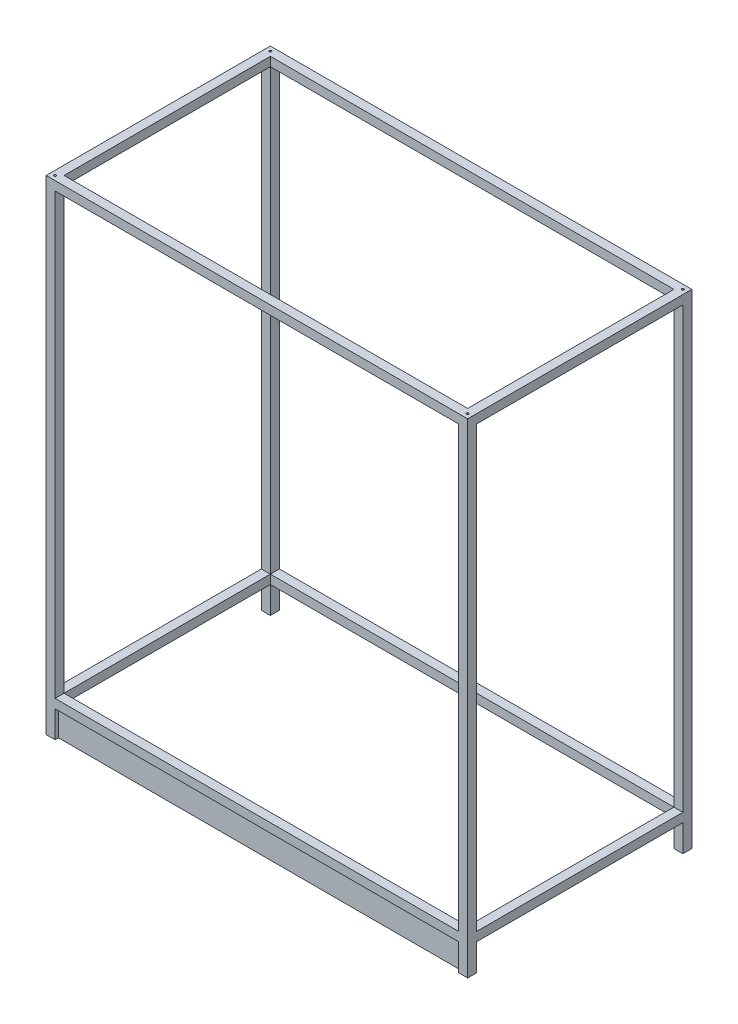
SolidWorks part; units mm, degrees
ref_plane "Front Plane" through (0, 0, 0) normal (0, 0, 1) x (1, 0, 0)
ref_plane "Top Plane" through (0, 0, 0) normal (0, 1, 0) x (1, 0, 0)
ref_plane "Right Plane" through (0, 0, 0) normal (1, 0, 0) x (0, 0, -1)
sketch "Sketch1" plane through (0, 0, 0) normal (0, 0, 1) x (1, 0, 0)
  line L1 (0, 0) -> (1193.8, 0)
  line L2 (0, 0) -> (0, 1371.6)
  line L3 (0, 1371.6) -> (1193.8, 1371.6)
  line L4 (1193.8, 0) -> (1193.8, 1371.6)
  dimension "D1" = 1193.8
  dimension "D2" = 1371.6
extrude "Extrude1" add sketch "Sketch1" along normal blind 635
sketch "Sketch2" plane through (0, 1371.6, 0) normal (0, 1, 0) x (1, 0, 0)
  line L0 (25.4, -609.6) -> (25.4, -635)
  line L1 (-656.59, 0) -> (656.59, 0) construction
  line L2 (25.4, 0) -> (25.4, -25.4)
  line L3 (1193.8, 0) -> (0, 0) construction
  line L4 (0, -635) -> (0, 0) construction
  line L5 (1168.4, 0) -> (1168.4, -25.4)
  line L6 (0, -609.6) -> (25.4, -609.6)
  line L7 (1193.8, -635) -> (1193.8, 0) construction
  line L8 (0, -25.4) -> (25.4, -25.4)
  line L9 (1193.8, -635) -> (0, -635) construction
  line L10 (1168.4, -25.4) -> (1193.8, -25.4)
  line L11 (1168.4, -609.6) -> (1193.8, -609.6)
  line L12 (1168.4, -609.6) -> (1168.4, -635)
  line L14 (1168.4, 0) -> (25.4, 0)
  line L15 (1193.8, -25.4) -> (1193.8, -609.6)
  line L16 (1168.4, -635) -> (25.4, -635)
  line L17 (0, -25.4) -> (0, -609.6)
sketch "Sketch4" plane through (0, 1371.6, 0) normal (0, 1, 0) x (1, 0, 0)
extrude "Extrude4" cut sketch "Sketch2" against normal blind 1270
sketch "Sketch6" plane through (0, 0, 25.4) normal (0, 0, 1) x (1, 0, 0)
  line L0 (0, 1371.6) -> (0, 1346.2)
  line L1 (0, 101.6) -> (0, 1371.6) construction
  line L2 (0, 1346.2) -> (25.4, 1346.2)
  line L3 (25.4, 101.6) -> (25.4, 1371.6) construction
  line L4 (25.4, 1346.2) -> (25.4, 1371.6)
  line L5 (25.4, 1371.6) -> (0, 1371.6) construction
  line L6 (25.4, 1371.6) -> (0, 1371.6)
  dimension "D1" = 25.4
extrude "Extrude5" add sketch "Sketch6" along normal up to surface (584.2 mm away) up to face at (12.7, 736.6, 609.6)
sketch "Sketch8" plane through (25.4, 0, 0) normal (1, 0, 0) x (0, 0, -1)
  line L1 (-635, 1371.6) -> (-609.6, 1371.6)
  line L2 (-635, 1371.6) -> (-635, 1346.2)
  line L3 (-635, 1346.2) -> (-609.6, 1346.2)
  line L4 (-609.6, 1371.6) -> (-609.6, 1346.2)
extrude "Extrude6" add sketch "Sketch8" along normal up to surface (1143 mm away) up to face at (1168.4, 736.6, 622.3)
sketch "Sketch9" plane through (0, 0, 609.6) normal (0, 0, -1) x (-1, 0, 0)
  line L1 (-1193.8, 1371.6) -> (-1168.4, 1371.6)
  line L2 (-1193.8, 1371.6) -> (-1193.8, 1346.2)
  line L3 (-1193.8, 1346.2) -> (-1168.4, 1346.2)
  line L4 (-1168.4, 1371.6) -> (-1168.4, 1346.2)
extrude "Extrude7" add sketch "Sketch9" along normal up to surface (584.2 mm away) up to face at (1181.1, 736.6, 25.4)
sketch "Sketch10" plane through (1168.4, 0, 0) normal (-1, 0, 0) x (0, 0, 1)
  line L1 (0, 1371.6) -> (25.4, 1371.6)
  line L2 (0, 1371.6) -> (0, 1346.2)
  line L3 (0, 1346.2) -> (25.4, 1346.2)
  line L4 (25.4, 1371.6) -> (25.4, 1346.2)
extrude "Extrude8" add sketch "Sketch10" along normal up to surface (1143 mm away) up to face at (25.4, 723.9, 622.3)
shell "Shell2" thickness 25.4
sketch "Sketch11" plane through (25.4, 0, 0) normal (1, 0, 0) x (0, 0, -1)
  line L1 (-25.4, 76.2) -> (-609.6, 76.2)
  line L2 (-25.4, 76.2) -> (-25.4, 0)
  line L3 (-25.4, 0) -> (-609.6, 0)
  line L4 (-609.6, 76.2) -> (-609.6, 0)
sketch "Sketch12" plane through (0, 0, 25.4) normal (0, 0, 1) x (1, 0, 0)
  line L1 (25.4, 76.2) -> (1168.4, 76.2)
  line L2 (25.4, 76.2) -> (25.4, 0)
  line L3 (25.4, 0) -> (1168.4, 0)
  line L4 (1168.4, 76.2) -> (1168.4, 0)
sketch "Sketch13" plane through (1168.4, 0, 0) normal (-1, 0, 0) x (0, 0, 1)
  line L1 (609.6, 76.2) -> (25.4, 76.2)
  line L2 (609.6, 76.2) -> (609.6, 0)
  line L3 (609.6, 0) -> (25.4, 0)
  line L4 (25.4, 76.2) -> (25.4, 0)
sketch "Sketch14" plane through (0, 0, 609.6) normal (0, 0, -1) x (-1, 0, 0)
  line L2 (-25.4, 0) -> (-1168.4, 0)
  line L3 (-25.4, 0) -> (-25.4, 76.2)
  line L4 (-25.4, 76.2) -> (-1168.4, 76.2)
  line L5 (-1168.4, 0) -> (-1168.4, 76.2)
sketch "Sketch17" plane through (0, 1371.6, 0) normal (0, 1, 0) x (1, 0, 0)
  circle A0 centre (1181.1, -622.3) radius 3.175
  circle A1 centre (1181.1, -12.7) radius 3.175
  circle A2 centre (12.7, -12.7) radius 3.175
  circle A3 centre (12.7, -622.3) radius 3.175
  dimension "D1" = 6.35
  dimension "D2" = 6.35
  dimension "D3" = 6.35
  dimension "D4" = 6.35
extrude "Extrude14" cut sketch "Sketch17" against normal through all contours A0 | A1 | A2 | A3
sketch "Sketch18" plane through (0, 0, 0) normal (-1, 0, 0) x (0, 0, 1)
  line L0 (635, 1371.6) -> (0, 1371.6) construction
  line L1 (0, 1371.6) -> (25.4, 1371.6)
  line L2 (0, 1371.6) -> (0, 0)
  line L3 (0, 0) -> (25.4, 0)
  line L4 (25.4, 1371.6) -> (25.4, 0)
  line L5 (25.4, 0) -> (609.6, 0)
  line L6 (25.4, 0) -> (25.4, 101.6)
  line L7 (25.4, 101.6) -> (609.6, 101.6)
  line L8 (609.6, 0) -> (609.6, 101.6)
  line L9 (609.6, 1371.6) -> (635, 1371.6)
  line L10 (609.6, 1371.6) -> (609.6, 0)
  line L11 (609.6, 0) -> (635, 0)
  line L12 (635, 1371.6) -> (635, 0)
  line L14 (25.4, 1371.6) -> (609.6, 1371.6)
  line L15 (25.4, 1371.6) -> (25.4, 1346.2)
  line L16 (25.4, 1346.2) -> (609.6, 1346.2)
  line L17 (609.6, 1371.6) -> (609.6, 1346.2)
  line L18 (25.4, 101.6) -> (609.6, 101.6)
  line L19 (25.4, 101.6) -> (25.4, 76.2)
  line L20 (25.4, 76.2) -> (609.6, 76.2)
  line L21 (609.6, 101.6) -> (609.6, 76.2)
sketch "Sketch19" plane through (0, 1371.6, 0) normal (0, 1, 0) x (1, 0, 0)
  line L0 (1193.8, -635) -> (0, -635) construction
  line L2 (0, -25.4) -> (0, -609.6)
  line L3 (25.4, -25.4) -> (0, -25.4)
  line L4 (25.4, -25.4) -> (25.4, -609.6)
  line L5 (25.4, -609.6) -> (1168.4, -609.6)
  line L6 (25.4, -25.4) -> (25.4, 0)
  line L7 (25.4, -635) -> (1168.4, -635)
  line L8 (1168.4, -609.6) -> (1193.8, -609.6)
  line L9 (1193.8, -635) -> (1193.8, 0) construction
  line L10 (1168.4, -609.6) -> (1168.4, -635)
  line L11 (1168.4, -609.6) -> (1168.4, -25.4)
  line L12 (1168.4, -25.4) -> (1193.8, -25.4)
  line L13 (1193.8, -609.6) -> (1193.8, -25.4)
  line L14 (1193.8, 0) -> (0, 0) construction
  line L15 (1168.4, -25.4) -> (25.4, -25.4)
  line L16 (1168.4, -25.4) -> (1168.4, 0)
  line L17 (1168.4, 0) -> (25.4, 0)
  line L18 (25.4, 0) -> (0, 0)
  line L19 (0, -25.4) -> (0, 0)
  line L20 (0, -609.6) -> (25.4, -609.6)
  line L21 (0, -609.6) -> (0, -635)
  line L22 (0, -635) -> (25.4, -635)
  line L23 (25.4, -609.6) -> (25.4, -635)
  line L24 (1168.4, -635) -> (1193.8, -635)
  line L25 (1193.8, -609.6) -> (1193.8, -635)
  line L26 (1168.4, 0) -> (1193.8, 0)
  line L27 (1193.8, -25.4) -> (1193.8, 0)
sketch "Sketch20" plane through (0, 0, 635) normal (0, 0, 1) x (1, 0, 0)
  line L0 (0, 0) -> (1193.8, 0) construction
  line L1 (0, 1371.6) -> (25.4, 1371.6)
  line L2 (0, 1371.6) -> (0, 0)
  line L3 (0, 0) -> (25.4, 0)
  line L4 (25.4, 1371.6) -> (25.4, 0)
  line L6 (25.4, 0) -> (1168.4, 0)
  line L7 (25.4, 0) -> (25.4, 101.6)
  line L8 (25.4, 101.6) -> (1168.4, 101.6)
  line L9 (1168.4, 0) -> (1168.4, 101.6)
  line L10 (1193.8, 0) -> (1168.4, 0)
  line L11 (1193.8, 0) -> (1193.8, 1371.6)
  line L12 (1193.8, 1371.6) -> (1168.4, 1371.6)
  line L13 (1168.4, 0) -> (1168.4, 1371.6)
  line L14 (25.4, 1371.6) -> (1168.4, 1371.6)
  line L15 (25.4, 1371.6) -> (25.4, 1346.2)
  line L16 (25.4, 1346.2) -> (1168.4, 1346.2)
  line L17 (1168.4, 1371.6) -> (1168.4, 1346.2)
  line L18 (25.4, 101.6) -> (25.4, 76.2)
  line L19 (25.4, 76.2) -> (1168.4, 76.2)
  line L20 (1168.4, 101.6) -> (1168.4, 76.2)
  line L21 (25.4, 76.2) -> (1168.4, 76.2)
  line L22 (25.4, 76.2) -> (25.4, 0)
  line L23 (25.4, 0) -> (1168.4, 0)
  line L24 (1168.4, 76.2) -> (1168.4, 0)
  dimension "D1" = 25.4
sketch "Sketch21" plane through (0, 101.6, 0) normal (0, 1, 0) x (1, 0, 0)
  line L1 (25.4, -635) -> (1168.4, -635)
  line L2 (25.4, -635) -> (25.4, -609.6)
  line L4 (1168.4, -635) -> (1168.4, -609.6)
  line L5 (1168.4, -25.4) -> (1193.8, -25.4)
  line L7 (1168.4, -609.6) -> (1193.8, -609.6)
  line L8 (1193.8, -25.4) -> (1193.8, -609.6)
  line L10 (1168.4, -25.4) -> (1168.4, 0)
  line L11 (1168.4, 0) -> (25.4, 0)
  line L12 (25.4, -25.4) -> (25.4, 0)
  line L13 (25.4, -25.4) -> (0, -25.4)
  line L15 (25.4, -609.6) -> (0, -609.6)
  line L16 (0, -25.4) -> (0, -609.6)
sketch "Sketch24" plane through (0, 101.6, 0) normal (0, 1, 0) x (1, 0, 0)
  line L1 (1168.4, -25.4) -> (25.4, -25.4)
  line L2 (1168.4, -25.4) -> (1168.4, -609.6)
  line L3 (1168.4, -609.6) -> (25.4, -609.6)
  line L4 (25.4, -25.4) -> (25.4, -609.6)
extrude "Extrude15" cut sketch "Sketch24" against normal blind 25.4
sketch "Sketch25" plane through (1193.8, 0, 0) normal (1, 0, 0) x (0, 0, -1)
  line L0 (-635, 0) -> (0, 0) construction
  line L1 (-609.6, 0) -> (-635, 0)
  line L2 (-609.6, 0) -> (-609.6, 1371.6)
  line L3 (-609.6, 1371.6) -> (-635, 1371.6)
  line L4 (-635, 0) -> (-635, 1371.6)
  line L6 (-609.6, 1371.6) -> (-25.4, 1371.6)
  line L7 (-609.6, 1371.6) -> (-609.6, 1346.2)
  line L8 (-609.6, 1346.2) -> (-25.4, 1346.2)
  line L9 (-25.4, 1371.6) -> (-25.4, 1346.2)
  line L10 (0, 1371.6) -> (-25.4, 1371.6)
  line L11 (0, 1371.6) -> (0, 0)
  line L12 (0, 0) -> (-25.4, 0)
  line L13 (-25.4, 1371.6) -> (-25.4, 0)
  line L14 (-609.6, 101.6) -> (-25.4, 101.6)
  line L15 (-609.6, 101.6) -> (-609.6, 76.2)
  line L16 (-609.6, 76.2) -> (-25.4, 76.2)
  line L17 (-25.4, 101.6) -> (-25.4, 76.2)
  line L18 (-609.6, 76.2) -> (-25.4, 76.2)
  line L19 (-609.6, 76.2) -> (-609.6, 0)
  line L20 (-609.6, 0) -> (-25.4, 0)
  line L21 (-25.4, 76.2) -> (-25.4, 0)
sketch "Sketch26" plane through (0, 0, 0) normal (0, 0, -1) x (-1, 0, 0)
  line L1 (-1168.4, 1371.6) -> (-1193.8, 1371.6)
  line L2 (-1168.4, 1371.6) -> (-1168.4, 0)
  line L3 (-1168.4, 0) -> (-1193.8, 0)
  line L4 (-1193.8, 1371.6) -> (-1193.8, 0)
  line L5 (-1168.4, 1371.6) -> (-25.4, 1371.6)
  line L6 (-1168.4, 1371.6) -> (-1168.4, 1346.2)
  line L7 (-1168.4, 1346.2) -> (-25.4, 1346.2)
  line L8 (-25.4, 1371.6) -> (-25.4, 1346.2)
  line L9 (0, 0) -> (-25.4, 0)
  line L10 (0, 0) -> (0, 1371.6)
  line L11 (0, 1371.6) -> (-25.4, 1371.6)
  line L12 (-25.4, 0) -> (-25.4, 1371.6)
  line L13 (-1168.4, 101.6) -> (-25.4, 101.6)
  line L14 (-1168.4, 101.6) -> (-1168.4, 76.2)
  line L15 (-1168.4, 76.2) -> (-25.4, 76.2)
  line L16 (-25.4, 101.6) -> (-25.4, 76.2)
  line L17 (-25.4, 76.2) -> (-1168.4, 76.2)
  line L18 (-25.4, 76.2) -> (-25.4, 0)
  line L19 (-25.4, 0) -> (-1168.4, 0)
  line L20 (-1168.4, 76.2) -> (-1168.4, 0)
  dimension "D1" = 25.4
sketch "Sketch29" plane through (0, 0, 0) normal (0, -1, 0) x (1, 0, 0)
  line L0 (1178.56, 609.6) -> (1183.64, 609.6)
  line L1 (1168.4, 609.6) -> (1193.8, 609.6)
  line L2 (1168.4, 635) -> (1168.4, 609.6)
  line L3 (1168.4, 635) -> (1193.8, 635)
  line L4 (1193.8, 609.6) -> (1193.8, 635)
  line L5 (1168.4, 624.84) -> (1168.4, 619.76)
extrude "Extrude16" cut sketch "Sketch12" against normal blind 38.1
extrude "Extrude17" cut sketch "Sketch13" against normal blind 38.1
extrude "Extrude18" cut sketch "Sketch14" against normal blind 38.1
extrude "Extrude19" cut sketch "Sketch11" against normal blind 38.1
sketch "Sketch30" plane through (0, 76.2, 0) normal (0, -1, 0) x (1, 0, 0)
  line L0 (25.4, 625.3711) -> (25.4, 619.7564)
  line L1 (25.4, 635) -> (25.4, 609.6) construction
  line L2 (25.4, 625.3711) -> (1168.4, 625.3711)
  line L3 (1168.4, 635) -> (1168.4, 609.6) construction
  line L4 (1168.4, 625.3711) -> (1168.4, 619.7564)
  line L5 (1168.4, 619.7564) -> (25.4, 619.7564)
extrude "Extrude20" add sketch "Sketch30" along normal up to surface (76.2 mm away) up to face at (12.7, 0, 625.475)
sketch "Sketch31" plane through (0, 76.2, 0) normal (0, -1, 0) x (1, 0, 0)
  line L0 (1193.8, 609.6) -> (1181.1, 609.6)
  line L1 (1193.8, 609.6) -> (1193.8, 25.4) construction
  line L2 (1193.8, 609.6) -> (1168.4, 609.6) construction
  line L3 (1181.1, 609.6) -> (1181.938, 609.6)
  line L4 (1181.938, 609.6) -> (1178.5554, 609.6)
  dimension "D1" = 0.838
